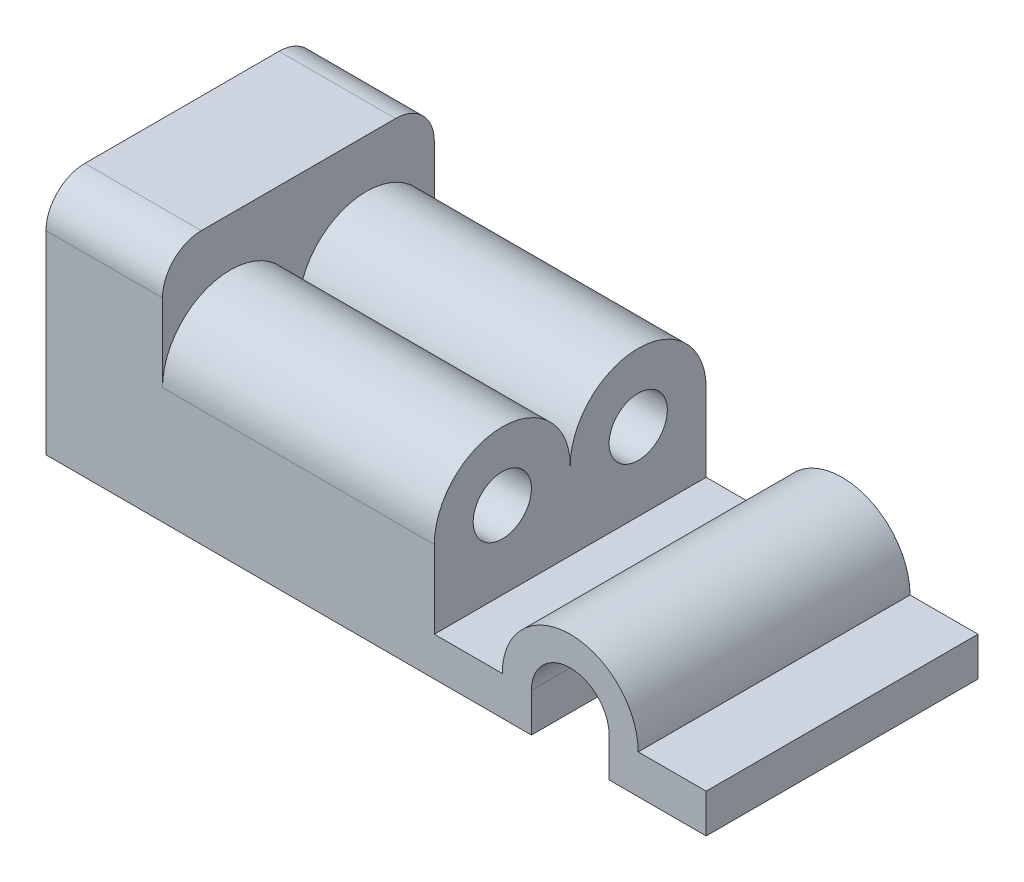
SolidWorks part; units mm, degrees
ref_plane "Front Plane" through (0, 0, 0) normal (0, 0, 1) x (1, 0, 0)
ref_plane "Top Plane" through (0, 0, 0) normal (0, 1, 0) x (1, 0, 0)
ref_plane "Right Plane" through (0, 0, 0) normal (1, 0, 0) x (0, 0, -1)
sketch "Sketch1" plane through (0, 0, 0) normal (0, 0, 1) x (1, 0, 0)
  line L0 (67.5, -20) -> (85, -20)
  line L1 (-85, 30) -> (-55, 30)
  line L2 (-85, 30) -> (-85, -30)
  line L3 (-85, -30) -> (40, -30)
  line L4 (85, -20) -> (85, -30)
  line L5 (40, -20) -> (40, -30)
  line L6 (60, -20) -> (60, -30)
  line L7 (15, -20) -> (32.5, -20)
  line L8 (-55, 30) -> (-55, 0)
  line L9 (-85, -20) -> (85, -20) construction
  line L10 (-55, 0) -> (15, 0)
  line L11 (15, 0) -> (15, -20)
  line L12 (-85, 0) -> (439.6096, 0) construction
  line L13 (-85, 30) -> (439.6096, 30) construction
  line L14 (60, -30) -> (85, -30)
  line L15 (15, 30) -> (15, -30) construction
  line L16 (-55, 30) -> (-55, -30) construction
  line L18 (-85, -30) -> (85, -30) construction
  arc A0 (60, -20) -> (40, -20) centre (50, -20) ccw
  arc A2 (67.5, -20) -> (32.5, -20) centre (50, -20) ccw
  point P0 (0, 0)
  point P6 (50, 30)
  point P7 (439.6096, -39.8152)
  point P8 (40, 30)
  point P10 (60, 30)
  point P17 (155.5346, -8.2616)
  point P19 (249.7701, -30)
  point P20 (67.5, -20)
  point P32 (109.0727, 0)
  point P33 (439.6096, 0)
  point P34 (439.6096, -39.8152)
  dimension "D6" = 10
  dimension "D8" = 17.5
  dimension "D1" = 70
  dimension "D2" = 60
  dimension "D3" = 30
  dimension "D5" = 15
  dimension "D9" = 50
  dimension "D10" = 85
  dimension "D4" = 30
  dimension "D7" = 10
extrude "Boss-Extrude1" add sketch "Sketch1" against normal blind 70
fillet "Fillet1" radius 10 1 edges at (-70, 30, 0)
fillet "Fillet2" radius 10 1 edges at (-70, 30, -70)
sketch "Sketch2" plane through (15, 0, 0) normal (1, 0, 0) x (0, 0, -1)
  line L2 (70, 0) -> (0, 0) construction
  line L5 (0, 0) -> (70, 0)
  arc A0 (35, 0) -> (0, 0) centre (17.5, 0) ccw
  arc A1 (70, 0) -> (35, 0) centre (52.5, 0) ccw
  line M7 (70, 0) -> (0, 0)
  dimension "D1" = 17.5
extrude "Boss-Extrude2" add sketch "Sketch2" against normal blind 70 contours L5 A0 | A1 M7
sketch "Sketch3" plane through (15, 0, 0) normal (1, 0, 0) x (0, 0, -1)
  circle A0 centre (17.5, 0) radius 7.5
  circle A1 centre (52.5, 0) radius 7.5
  dimension "D1" = 15
  dimension "D2" = 15
extrude "Cut-Extrude1" cut sketch "Sketch3" against normal blind 185
